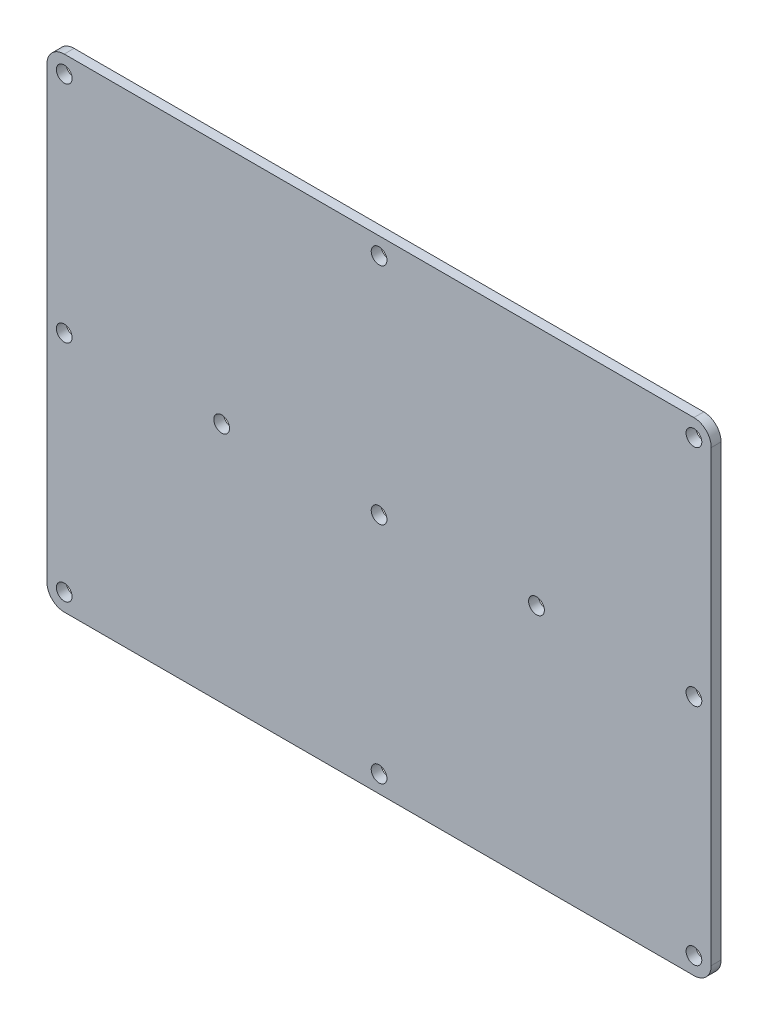
SolidWorks part; units mm, degrees
ref_plane "Front Plane" through (0, 0, 0) normal (0, 0, 1) x (1, 0, 0)
ref_plane "Top Plane" through (0, 0, 0) normal (0, 1, 0) x (1, 0, 0)
ref_plane "Right Plane" through (0, 0, 0) normal (1, 0, 0) x (0, 0, -1)
sketch "Sketch1" plane through (0, 0, 0) normal (0, 0, 1) x (1, 0, 0)
  line L0 (-152.4, 127) -> (-76.2, 127) construction
  line L1 (-152.4, 152.4) -> (152.4, 152.4)
  line L2 (-152.4, 152.4) -> (-152.4, -152.4)
  line L3 (-152.4, -152.4) -> (152.4, -152.4)
  line L4 (152.4, 152.4) -> (152.4, -152.4)
  line L5 (-76.2, 127) -> (-25.4, 127) construction
  line L6 (-25.4, 127) -> (25.4, 127) construction
  line L7 (25.4, 127) -> (76.2, 127) construction
  line L8 (76.2, 127) -> (152.4, 127) construction
  line L9 (-152.4, 0) -> (152.4, 0) construction
  line L10 (0, 152.4) -> (0, -152.4) construction
  line L11 (-118.11, 152.4) -> (-118.11, -152.4) construction
  line L12 (-152.4, -127) -> (152.4, -127) construction
  line L13 (127, 152.4) -> (127, -152.4) construction
  line L14 (-50.8, 152.4) -> (-50.8, -152.4) construction
  line L15 (50.8, 152.4) -> (50.8, -152.4) construction
  line L16 (-101.6, 152.4) -> (-101.6, -152.4) construction
  line L17 (-95.25, 66.04) -> (-57.15, 66.04) construction
  line L18 (-95.25, 66.04) -> (-95.25, -66.04) construction
  line L19 (-95.25, -66.04) -> (-57.15, -66.04) construction
  line L20 (-57.15, 66.04) -> (-57.15, -66.04) construction
  line L21 (-44.45, 66.04) -> (-6.35, 66.04) construction
  line L22 (-44.45, 66.04) -> (-44.45, -66.04) construction
  line L23 (-44.45, -66.04) -> (-6.35, -66.04) construction
  line L24 (-6.35, 66.04) -> (-6.35, -66.04) construction
  line L25 (6.35, 66.04) -> (44.45, 66.04) construction
  line L26 (6.35, 66.04) -> (6.35, -66.04) construction
  line L27 (6.35, -66.04) -> (44.45, -66.04) construction
  line L28 (44.45, 66.04) -> (44.45, -66.04) construction
  line L29 (57.15, 66.04) -> (95.25, 66.04) construction
  line L30 (57.15, 66.04) -> (57.15, -66.04) construction
  line L31 (57.15, -66.04) -> (95.25, -66.04) construction
  line L32 (95.25, 66.04) -> (95.25, -66.04) construction
  line L33 (101.6, 152.4) -> (101.6, -152.4) construction
  line L34 (-152.4, 120.65) -> (152.4, 120.65) construction
  line L35 (-101.6, 39.7057) -> (-95.25, 39.7057) construction
  line L36 (-57.15, 39.7057) -> (-50.8, 39.7057) construction
  line L37 (-76.2, 66.04) -> (-76.2, 0) construction
  line L38 (-76.2, 0) -> (-76.2, -66.04) construction
  line L39 (-152.4, 72.39) -> (152.4, 72.39) construction
  line L40 (-152.4, -72.39) -> (152.4, -72.39) construction
  line L41 (-76.2, 66.04) -> (-76.2, 72.39) construction
  line L42 (-95.25, -66.04) -> (-95.25, -72.39) construction
  line L43 (95.25, 39.7057) -> (101.6, 39.7057) construction
  line L44 (-95.25, 111.76) -> (-57.15, 111.76) construction
  line L45 (-57.15, 111.76) -> (-57.15, 118.4779) construction
  line L46 (-94.0266, 120.65) -> (-78.1749, 130.2582) construction
  line L47 (-95.25, 111.76) -> (-95.25, 118.4779) construction
  line L48 (-58.3734, 120.65) -> (-74.2251, 130.2582) construction
  line L49 (-107.3169, 130.81) -> (-83.1894, 130.81) construction
  line L50 (-6.35, 111.76) -> (-6.35, 118.4779) construction
  line L51 (-7.5734, 120.65) -> (-23.4251, 130.2582) construction
  line L52 (-43.2266, 120.65) -> (-27.3749, 130.2582) construction
  line L53 (-44.45, 111.76) -> (-44.45, 118.4779) construction
  line L54 (-6.35, 111.76) -> (-44.45, 111.76) construction
  line L55 (44.45, 111.76) -> (44.45, 118.4779) construction
  line L56 (43.2266, 120.65) -> (27.3749, 130.2582) construction
  line L57 (7.5734, 120.65) -> (23.4251, 130.2582) construction
  line L58 (6.35, 111.76) -> (6.35, 118.4779) construction
  line L59 (6.35, 111.76) -> (44.45, 111.76) construction
  line L60 (95.25, 111.76) -> (57.15, 111.76) construction
  line L61 (95.25, 111.76) -> (95.25, 118.4779) construction
  line L62 (94.0266, 120.65) -> (78.1749, 130.2582) construction
  line L63 (58.3734, 120.65) -> (74.2251, 130.2582) construction
  line L64 (57.15, 111.76) -> (57.15, 118.4779) construction
  line L65 (-95.25, -111.76) -> (-95.25, -118.4779) construction
  line L66 (-94.0266, -120.65) -> (-78.1749, -130.2582) construction
  line L67 (-58.3734, -120.65) -> (-74.2251, -130.2582) construction
  line L68 (-95.25, -111.76) -> (-57.15, -111.76) construction
  line L69 (-57.15, -111.76) -> (-57.15, -118.4779) construction
  line L70 (-44.45, -111.76) -> (-44.45, -118.4779) construction
  line L71 (-43.2266, -120.65) -> (-27.3749, -130.2582) construction
  line L72 (-6.35, -111.76) -> (-44.45, -111.76) construction
  line L73 (-7.5734, -120.65) -> (-23.4251, -130.2582) construction
  line L74 (-6.35, -111.76) -> (-6.35, -118.4779) construction
  line L75 (6.35, -111.76) -> (6.35, -118.4779) construction
  line L76 (7.5734, -120.65) -> (23.4251, -130.2582) construction
  line L77 (43.2266, -120.65) -> (27.3749, -130.2582) construction
  line L78 (6.35, -111.76) -> (44.45, -111.76) construction
  line L79 (44.45, -111.76) -> (44.45, -118.4779) construction
  line L80 (57.15, -111.76) -> (57.15, -118.4779) construction
  line L81 (58.3734, -120.65) -> (74.2251, -130.2582) construction
  line L82 (94.0266, -120.65) -> (78.1749, -130.2582) construction
  line L83 (95.25, -111.76) -> (57.15, -111.76) construction
  line L84 (95.25, -111.76) -> (95.25, -118.4779) construction
  line L85 (-152.4, 97.79) -> (152.4, 97.79) construction
  line L86 (-50.8, 39.7057) -> (-44.45, 39.7057) construction
  line L87 (-127, 152.4) -> (-127, -152.4) construction
  line L89 (-95.25, 101.6) -> (-92.3192, 101.6) construction
  line L90 (-95.25, 101.6) -> (-95.25, -101.6) construction
  line L96 (-90.8538, 101.6) -> (-90.8538, 68.58) construction
  line L97 (-89.3885, 101.6) -> (-89.3885, 68.58) construction
  line L98 (-92.3192, 101.6) -> (-92.3192, 68.58) construction
  line L99 (-83.5269, 101.6) -> (-83.5269, 68.58) construction
  line L100 (-86.4577, 101.6) -> (-86.4577, 68.58) construction
  line L101 (-89.3885, 101.6) -> (-86.4577, 101.6) construction
  line L102 (-77.6654, 101.6) -> (-77.6654, 68.58) construction
  line L103 (-80.5962, 101.6) -> (-80.5962, 68.58) construction
  line L104 (-83.5269, 101.6) -> (-80.5962, 101.6) construction
  line L105 (-71.8038, 101.6) -> (-71.8038, 68.58) construction
  line L106 (-74.7346, 101.6) -> (-74.7346, 68.58) construction
  line L107 (-77.6654, 101.6) -> (-74.7346, 101.6) construction
  line L108 (-65.9423, 101.6) -> (-65.9423, 68.58) construction
  line L109 (-68.8731, 101.6) -> (-68.8731, 68.58) construction
  line L110 (-71.8038, 101.6) -> (-68.8731, 101.6) construction
  line L111 (-60.0808, 101.6) -> (-60.0808, 68.58) construction
  line L112 (-63.0115, 101.6) -> (-63.0115, 68.58) construction
  line L113 (-65.9423, 101.6) -> (-63.0115, 101.6) construction
  line L114 (-57.15, -101.6) -> (-57.15, 101.6) construction
  line L115 (-60.0808, 101.6) -> (-57.15, 101.6) construction
  line L116 (-92.3192, 68.58) -> (-89.3885, 68.58) construction
  line L117 (-60.0808, -101.6) -> (-57.15, -101.6) construction
  line L118 (-60.0808, -101.6) -> (-60.0808, -68.58) construction
  line L119 (-63.0115, -101.6) -> (-63.0115, -68.58) construction
  line L120 (-65.9423, -101.6) -> (-65.9423, -68.58) construction
  line L121 (-65.9423, -101.6) -> (-63.0115, -101.6) construction
  line L122 (-68.8731, -101.6) -> (-68.8731, -68.58) construction
  line L123 (-71.8038, -101.6) -> (-68.8731, -101.6) construction
  line L124 (-71.8038, -101.6) -> (-71.8038, -68.58) construction
  line L125 (-74.7346, -101.6) -> (-74.7346, -68.58) construction
  line L126 (-77.6654, -101.6) -> (-74.7346, -101.6) construction
  line L127 (-77.6654, -101.6) -> (-77.6654, -68.58) construction
  line L128 (-80.5962, -101.6) -> (-80.5962, -68.58) construction
  line L129 (-83.5269, -101.6) -> (-80.5962, -101.6) construction
  line L130 (-83.5269, -101.6) -> (-83.5269, -68.58) construction
  line L131 (-86.4577, -101.6) -> (-86.4577, -68.58) construction
  line L132 (-89.3885, -101.6) -> (-86.4577, -101.6) construction
  line L133 (-89.3885, -101.6) -> (-89.3885, -68.58) construction
  line L134 (-92.3192, -101.6) -> (-92.3192, -68.58) construction
  line L135 (-95.25, -101.6) -> (-92.3192, -101.6) construction
  line L136 (-9.2808, 68.58) -> (-12.2115, 68.58) construction
  line L137 (6.35, 66.04) -> (44.45, 66.04) construction
  line L138 (-6.35, -66.04) -> (-6.35, -72.39) construction
  line L139 (-25.4, 66.04) -> (-25.4, 72.39) construction
  line L140 (-25.4, 0) -> (-25.4, -66.04) construction
  line L141 (-25.4, 66.04) -> (-25.4, 0) construction
  line L142 (-44.45, 66.04) -> (-44.45, -66.04) construction
  line L143 (-6.35, -66.04) -> (-44.45, -66.04) construction
  line L144 (-6.35, 66.04) -> (-6.35, -66.04) construction
  line L145 (-6.35, 66.04) -> (-44.45, 66.04) construction
  line L146 (-6.35, -101.6) -> (-9.2808, -101.6) construction
  line L147 (-9.2808, -101.6) -> (-9.2808, -68.58) construction
  line L148 (-12.2115, -101.6) -> (-12.2115, -68.58) construction
  line L149 (-12.2115, -101.6) -> (-15.1423, -101.6) construction
  line L150 (-15.1423, -101.6) -> (-15.1423, -68.58) construction
  line L151 (-18.0731, -101.6) -> (-18.0731, -68.58) construction
  line L152 (-18.0731, -101.6) -> (-21.0038, -101.6) construction
  line L153 (-21.0038, -101.6) -> (-21.0038, -68.58) construction
  line L154 (-23.9346, -101.6) -> (-23.9346, -68.58) construction
  line L155 (-23.9346, -101.6) -> (-26.8654, -101.6) construction
  line L156 (-26.8654, -101.6) -> (-26.8654, -68.58) construction
  line L157 (-29.7962, -101.6) -> (-29.7962, -68.58) construction
  line L158 (-29.7962, -101.6) -> (-32.7269, -101.6) construction
  line L159 (-32.7269, -101.6) -> (-32.7269, -68.58) construction
  line L160 (-35.6577, -101.6) -> (-38.5885, -101.6) construction
  line L161 (-35.6577, -101.6) -> (-35.6577, -68.58) construction
  line L162 (-38.5885, -101.6) -> (-38.5885, -68.58) construction
  line L163 (-41.5192, -101.6) -> (-41.5192, -68.58) construction
  line L164 (-41.5192, -101.6) -> (-44.45, -101.6) construction
  line L165 (-41.5192, 101.6) -> (-44.45, 101.6) construction
  line L166 (-44.45, -101.6) -> (-44.45, 101.6) construction
  line L167 (-35.6577, 101.6) -> (-38.5885, 101.6) construction
  line L168 (-38.5885, 101.6) -> (-38.5885, 68.58) construction
  line L169 (-41.5192, 101.6) -> (-41.5192, 68.58) construction
  line L170 (-29.7962, 101.6) -> (-32.7269, 101.6) construction
  line L171 (-32.7269, 101.6) -> (-32.7269, 68.58) construction
  line L172 (-35.6577, 101.6) -> (-35.6577, 68.58) construction
  line L173 (-23.9346, 101.6) -> (-26.8654, 101.6) construction
  line L174 (-26.8654, 101.6) -> (-26.8654, 68.58) construction
  line L175 (-29.7962, 101.6) -> (-29.7962, 68.58) construction
  line L176 (-18.0731, 101.6) -> (-21.0038, 101.6) construction
  line L177 (-21.0038, 101.6) -> (-21.0038, 68.58) construction
  line L178 (-23.9346, 101.6) -> (-23.9346, 68.58) construction
  line L179 (-12.2115, 101.6) -> (-15.1423, 101.6) construction
  line L180 (-15.1423, 101.6) -> (-15.1423, 68.58) construction
  line L181 (-18.0731, 101.6) -> (-18.0731, 68.58) construction
  line L182 (-9.2808, 101.6) -> (-9.2808, 68.58) construction
  line L183 (-12.2115, 101.6) -> (-12.2115, 68.58) construction
  line L184 (-6.35, 101.6) -> (-6.35, -101.6) construction
  line L185 (-6.35, 101.6) -> (-9.2808, 101.6) construction
  line L186 (6.35, 66.04) -> (6.35, -66.04) construction
  line L187 (6.35, -66.04) -> (44.45, -66.04) construction
  line L188 (44.45, 66.04) -> (44.45, -66.04) construction
  line L189 (25.4, 66.04) -> (25.4, 0) construction
  line L190 (25.4, 0) -> (25.4, -66.04) construction
  line L191 (25.4, 66.04) -> (25.4, 72.39) construction
  line L192 (6.35, -66.04) -> (6.35, -72.39) construction
  line L193 (9.2808, 68.58) -> (12.2115, 68.58) construction
  line L194 (6.35, 66.04) -> (6.35, -66.04) construction
  line L195 (44.45, -66.04) -> (6.35, -66.04) construction
  line L196 (44.45, 66.04) -> (44.45, -66.04) construction
  line L197 (44.45, 66.04) -> (6.35, 66.04) construction
  line L198 (6.35, 101.6) -> (9.2808, 101.6) construction
  line L199 (6.35, 101.6) -> (6.35, -101.6) construction
  line L200 (12.2115, 101.6) -> (12.2115, 68.58) construction
  line L201 (9.2808, 101.6) -> (9.2808, 68.58) construction
  line L202 (18.0731, 101.6) -> (18.0731, 68.58) construction
  line L203 (15.1423, 101.6) -> (15.1423, 68.58) construction
  line L204 (12.2115, 101.6) -> (15.1423, 101.6) construction
  line L205 (23.9346, 101.6) -> (23.9346, 68.58) construction
  line L206 (21.0038, 101.6) -> (21.0038, 68.58) construction
  line L207 (18.0731, 101.6) -> (21.0038, 101.6) construction
  line L208 (29.7962, 101.6) -> (29.7962, 68.58) construction
  line L209 (26.8654, 101.6) -> (26.8654, 68.58) construction
  line L210 (23.9346, 101.6) -> (26.8654, 101.6) construction
  line L211 (35.6577, 101.6) -> (35.6577, 68.58) construction
  line L212 (32.7269, 101.6) -> (32.7269, 68.58) construction
  line L213 (29.7962, 101.6) -> (32.7269, 101.6) construction
  line L214 (41.5192, 101.6) -> (41.5192, 68.58) construction
  line L215 (38.5885, 101.6) -> (38.5885, 68.58) construction
  line L216 (35.6577, 101.6) -> (38.5885, 101.6) construction
  line L217 (44.45, -101.6) -> (44.45, 101.6) construction
  line L218 (41.5192, 101.6) -> (44.45, 101.6) construction
  line L219 (41.5192, -101.6) -> (44.45, -101.6) construction
  line L220 (41.5192, -101.6) -> (41.5192, -68.58) construction
  line L221 (38.5885, -101.6) -> (38.5885, -68.58) construction
  line L222 (35.6577, -101.6) -> (35.6577, -68.58) construction
  line L223 (35.6577, -101.6) -> (38.5885, -101.6) construction
  line L224 (32.7269, -101.6) -> (32.7269, -68.58) construction
  line L225 (29.7962, -101.6) -> (32.7269, -101.6) construction
  line L226 (29.7962, -101.6) -> (29.7962, -68.58) construction
  line L227 (26.8654, -101.6) -> (26.8654, -68.58) construction
  line L228 (23.9346, -101.6) -> (26.8654, -101.6) construction
  line L229 (23.9346, -101.6) -> (23.9346, -68.58) construction
  line L230 (21.0038, -101.6) -> (21.0038, -68.58) construction
  line L231 (18.0731, -101.6) -> (21.0038, -101.6) construction
  line L232 (18.0731, -101.6) -> (18.0731, -68.58) construction
  line L233 (15.1423, -101.6) -> (15.1423, -68.58) construction
  line L234 (12.2115, -101.6) -> (15.1423, -101.6) construction
  line L235 (12.2115, -101.6) -> (12.2115, -68.58) construction
  line L236 (9.2808, -101.6) -> (9.2808, -68.58) construction
  line L237 (6.35, -101.6) -> (9.2808, -101.6) construction
  line L238 (57.15, 66.04) -> (95.25, 66.04) construction
  line L239 (57.15, 66.04) -> (57.15, -66.04) construction
  line L240 (57.15, -66.04) -> (95.25, -66.04) construction
  line L241 (95.25, 66.04) -> (95.25, -66.04) construction
  line L242 (92.3192, 68.58) -> (89.3885, 68.58) construction
  line L243 (95.25, -66.04) -> (95.25, -72.39) construction
  line L244 (76.2, 66.04) -> (76.2, 72.39) construction
  line L245 (76.2, 0) -> (76.2, -66.04) construction
  line L246 (76.2, 66.04) -> (76.2, 0) construction
  line L247 (57.15, 66.04) -> (57.15, -66.04) construction
  line L248 (95.25, -66.04) -> (57.15, -66.04) construction
  line L249 (95.25, 66.04) -> (95.25, -66.04) construction
  line L250 (95.25, 66.04) -> (57.15, 66.04) construction
  line L251 (57.15, 66.04) -> (57.15, -66.04) construction
  line L252 (95.25, -66.04) -> (57.15, -66.04) construction
  line L253 (95.25, 66.04) -> (95.25, -66.04) construction
  line L254 (95.25, 66.04) -> (57.15, 66.04) construction
  line L255 (95.25, -101.6) -> (92.3192, -101.6) construction
  line L256 (92.3192, -101.6) -> (92.3192, -68.58) construction
  line L257 (89.3885, -101.6) -> (89.3885, -68.58) construction
  line L258 (89.3885, -101.6) -> (86.4577, -101.6) construction
  line L259 (86.4577, -101.6) -> (86.4577, -68.58) construction
  line L260 (83.5269, -101.6) -> (83.5269, -68.58) construction
  line L261 (83.5269, -101.6) -> (80.5962, -101.6) construction
  line L262 (80.5962, -101.6) -> (80.5962, -68.58) construction
  line L263 (77.6654, -101.6) -> (77.6654, -68.58) construction
  line L264 (77.6654, -101.6) -> (74.7346, -101.6) construction
  line L265 (74.7346, -101.6) -> (74.7346, -68.58) construction
  line L266 (71.8038, -101.6) -> (71.8038, -68.58) construction
  line L267 (71.8038, -101.6) -> (68.8731, -101.6) construction
  line L268 (68.8731, -101.6) -> (68.8731, -68.58) construction
  line L269 (65.9423, -101.6) -> (63.0115, -101.6) construction
  line L270 (65.9423, -101.6) -> (65.9423, -68.58) construction
  line L271 (63.0115, -101.6) -> (63.0115, -68.58) construction
  line L272 (60.0808, -101.6) -> (60.0808, -68.58) construction
  line L273 (60.0808, -101.6) -> (57.15, -101.6) construction
  line L274 (60.0808, 101.6) -> (57.15, 101.6) construction
  line L275 (57.15, -101.6) -> (57.15, 101.6) construction
  line L276 (65.9423, 101.6) -> (63.0115, 101.6) construction
  line L277 (63.0115, 101.6) -> (63.0115, 68.58) construction
  line L278 (60.0808, 101.6) -> (60.0808, 68.58) construction
  line L279 (71.8038, 101.6) -> (68.8731, 101.6) construction
  line L280 (68.8731, 101.6) -> (68.8731, 68.58) construction
  line L281 (65.9423, 101.6) -> (65.9423, 68.58) construction
  line L282 (77.6654, 101.6) -> (74.7346, 101.6) construction
  line L283 (74.7346, 101.6) -> (74.7346, 68.58) construction
  line L284 (71.8038, 101.6) -> (71.8038, 68.58) construction
  line L285 (83.5269, 101.6) -> (80.5962, 101.6) construction
  line L286 (80.5962, 101.6) -> (80.5962, 68.58) construction
  line L287 (77.6654, 101.6) -> (77.6654, 68.58) construction
  line L288 (89.3885, 101.6) -> (86.4577, 101.6) construction
  line L289 (86.4577, 101.6) -> (86.4577, 68.58) construction
  line L290 (83.5269, 101.6) -> (83.5269, 68.58) construction
  line L291 (92.3192, 101.6) -> (92.3192, 68.58) construction
  line L292 (89.3885, 101.6) -> (89.3885, 68.58) construction
  line L293 (95.25, 101.6) -> (95.25, -101.6) construction
  line L294 (95.25, 101.6) -> (92.3192, 101.6) construction
  line L295 (-101.6, 39.7057) -> (-107.95, 39.7057) construction
  line L296 (-101.6, 78.74) -> (101.6, 78.74)
  line L298 (-101.6, -78.74) -> (101.6, -78.74)
  line L300 (-97.0611, 78.74) -> (-97.0611, 72.39) construction
  line L301 (-110.49, 22.225) -> (-120.65, 22.225) construction
  line L302 (-127, 15.875) -> (-127, -15.875) construction
  line L303 (-120.65, -22.225) -> (-110.49, -22.225) construction
  line L304 (-90.964, 120.65) -> (-61.436, 120.65) construction
  line L305 (-90.964, 122.2375) -> (-61.436, 122.2375) construction
  line L306 (-90.964, 119.0625) -> (-61.436, 119.0625) construction
  line L307 (-10.636, 120.65) -> (-40.164, 120.65) construction
  line L308 (-10.636, 122.2375) -> (-40.164, 122.2375) construction
  line L309 (-10.636, 119.0625) -> (-40.164, 119.0625) construction
  line L310 (10.636, 120.65) -> (40.164, 120.65) construction
  line L311 (10.636, 122.2375) -> (40.164, 122.2375) construction
  line L312 (10.636, 119.0625) -> (40.164, 119.0625) construction
  line L313 (90.964, 120.65) -> (61.436, 120.65) construction
  line L314 (90.964, 122.2375) -> (61.436, 122.2375) construction
  line L315 (90.964, 119.0625) -> (61.436, 119.0625) construction
  line L316 (90.964, -120.65) -> (61.436, -120.65) construction
  line L317 (90.964, -122.2375) -> (61.436, -122.2375) construction
  line L318 (90.964, -119.0625) -> (61.436, -119.0625) construction
  line L319 (10.636, -120.65) -> (40.164, -120.65) construction
  line L320 (10.636, -122.2375) -> (40.164, -122.2375) construction
  line L321 (10.636, -119.0625) -> (40.164, -119.0625) construction
  line L322 (-10.636, -120.65) -> (-40.164, -120.65) construction
  line L323 (-10.636, -122.2375) -> (-40.164, -122.2375) construction
  line L324 (-10.636, -119.0625) -> (-40.164, -119.0625) construction
  line L325 (-90.964, -120.65) -> (-61.436, -120.65) construction
  line L326 (-90.964, -122.2375) -> (-61.436, -122.2375) construction
  line L327 (-90.964, -119.0625) -> (-61.436, -119.0625) construction
  line L328 (-6.35, 111.125) -> (-6.35, 92.075) construction
  line L329 (-95.25, 111.125) -> (-57.15, 111.125) construction
  line L330 (-95.25, 111.125) -> (-95.25, 92.075) construction
  line L331 (-95.25, 92.075) -> (-57.15, 92.075) construction
  line L332 (-57.15, 111.125) -> (-57.15, 92.075) construction
  line L333 (-6.35, 111.125) -> (-44.45, 111.125) construction
  line L334 (-44.45, 111.125) -> (-44.45, 92.075) construction
  line L335 (-6.35, 92.075) -> (-44.45, 92.075) construction
  line L336 (95.25, 92.075) -> (57.15, 92.075) construction
  line L337 (95.25, 111.125) -> (95.25, 92.075)
  line L338 (95.25, 111.125) -> (57.15, 111.125) construction
  line L339 (57.15, 111.125) -> (57.15, 92.075) construction
  line L340 (44.45, 111.125) -> (44.45, 92.075) construction
  line L341 (6.35, 92.075) -> (44.45, 92.075) construction
  line L342 (6.35, 111.125) -> (44.45, 111.125) construction
  line L343 (6.35, 111.125) -> (6.35, 92.075) construction
  line L344 (-95.25, -92.075) -> (-57.15, -92.075) construction
  line L345 (-95.25, -111.125) -> (-95.25, -92.075) construction
  line L346 (-95.25, -111.125) -> (-57.15, -111.125) construction
  line L347 (-57.15, -111.125) -> (-57.15, -92.075) construction
  line L348 (-44.45, -111.125) -> (-44.45, -92.075) construction
  line L349 (-6.35, -92.075) -> (-44.45, -92.075) construction
  line L350 (-6.35, -111.125) -> (-44.45, -111.125) construction
  line L351 (-6.35, -111.125) -> (-6.35, -92.075) construction
  line L352 (6.35, -111.125) -> (6.35, -92.075) construction
  line L353 (6.35, -92.075) -> (44.45, -92.075) construction
  line L354 (6.35, -111.125) -> (44.45, -111.125) construction
  line L355 (44.45, -111.125) -> (44.45, -92.075) construction
  line L356 (57.15, -111.125) -> (57.15, -92.075) construction
  line L357 (95.25, -111.125) -> (57.15, -111.125) construction
  line L358 (95.25, -111.125) -> (95.25, -92.075) construction
  line L359 (95.25, -92.075) -> (57.15, -92.075) construction
  line L360 (-107.95, 72.39) -> (-107.95, 24.765)
  line L361 (-107.95, 22.225) -> (-107.95, -22.225) construction
  line L362 (-107.95, -24.765) -> (-107.95, -72.39)
  line L363 (3.659, 78.74) -> (3.659, -78.74) construction
  line L364 (120.65, -22.225) -> (110.49, -22.225) construction
  line L365 (127, 15.875) -> (127, -15.875) construction
  line L366 (110.49, 22.225) -> (120.65, 22.225) construction
  line L367 (107.95, 72.39) -> (107.95, 24.765)
  line L368 (107.95, -24.765) -> (107.95, -72.39)
  line L369 (-107.95, 24.765) -> (-107.95, -24.765)
  line L370 (107.95, 24.765) -> (107.95, -24.765)
  line L371 (-101.6, 77.978) -> (101.6, 77.978)
  line L372 (107.188, 72.39) -> (107.188, 24.765)
  line L373 (107.188, 24.765) -> (107.188, -24.765)
  line L374 (107.188, -24.765) -> (107.188, -72.39)
  line L375 (-101.6, -77.978) -> (101.6, -77.978)
  line L376 (-107.188, -24.765) -> (-107.188, -72.39)
  line L377 (-107.188, 24.765) -> (-107.188, -24.765)
  line L378 (-107.188, 72.39) -> (-107.188, 24.765)
  circle A0 centre (-76.2, 127) radius 2.5527 construction
  circle A1 centre (-25.4, 127) radius 2.5527 construction
  circle A2 centre (25.4, 127) radius 2.5527 construction
  circle A3 centre (76.2, 127) radius 2.5527 construction
  circle A4 centre (-101.6, 0) radius 2.54
  circle A5 centre (-50.8, 0) radius 2.54
  circle A6 centre (0, 0) radius 2.54
  circle A7 centre (101.6, 0) radius 2.54
  circle A8 centre (50.8, 0) radius 2.54
  circle A9 centre (-50.8, 127) radius 2.54
  circle A10 centre (0, 127) radius 2.54
  circle A11 centre (50.8, 127) radius 2.54
  circle A12 centre (-101.6, 72.39) radius 2.54
  circle A13 centre (0, 72.39) radius 2.54
  circle A14 centre (101.6, 72.39) radius 2.54
  circle A15 centre (-101.6, -72.39) radius 2.54
  circle A16 centre (0, -72.39) radius 2.54
  circle A17 centre (101.6, -72.39) radius 2.54
  arc A18 (-74.2251, 130.2582) -> (-78.1749, 130.2582) centre (-76.2, 127) ccw construction
  arc A19 (-57.15, 118.4779) -> (-58.3734, 120.65) centre (-59.69, 118.4779) ccw construction
  arc A20 (-95.25, 118.4779) -> (-94.0266, 120.65) centre (-92.71, 118.4779) cw construction
  arc A21 (-6.35, 118.4779) -> (-7.5734, 120.65) centre (-8.89, 118.4779) ccw construction
  arc A22 (-27.3749, 130.2582) -> (-23.4251, 130.2582) centre (-25.4, 127) cw construction
  arc A23 (-44.45, 118.4779) -> (-43.2266, 120.65) centre (-41.91, 118.4779) cw construction
  arc A24 (44.45, 118.4779) -> (43.2266, 120.65) centre (41.91, 118.4779) ccw construction
  arc A25 (27.3749, 130.2582) -> (23.4251, 130.2582) centre (25.4, 127) ccw construction
  arc A26 (6.35, 118.4779) -> (7.5734, 120.65) centre (8.89, 118.4779) cw construction
  arc A27 (95.25, 118.4779) -> (94.0266, 120.65) centre (92.71, 118.4779) ccw construction
  arc A28 (74.2251, 130.2582) -> (78.1749, 130.2582) centre (76.2, 127) cw construction
  arc A29 (57.15, 118.4779) -> (58.3734, 120.65) centre (59.69, 118.4779) cw construction
  circle A30 centre (-76.2, -127) radius 2.5527 construction
  circle A31 centre (-25.4, -127) radius 2.5527 construction
  circle A32 centre (25.4, -127) radius 2.5527 construction
  circle A33 centre (76.2, -127) radius 2.5527 construction
  arc A34 (-95.25, -118.4779) -> (-94.0266, -120.65) centre (-92.71, -118.4779) ccw construction
  arc A35 (-74.2251, -130.2582) -> (-78.1749, -130.2582) centre (-76.2, -127) cw construction
  arc A36 (-57.15, -118.4779) -> (-58.3734, -120.65) centre (-59.69, -118.4779) cw construction
  arc A37 (-44.45, -118.4779) -> (-43.2266, -120.65) centre (-41.91, -118.4779) ccw construction
  arc A38 (-27.3749, -130.2582) -> (-23.4251, -130.2582) centre (-25.4, -127) ccw construction
  arc A39 (-6.35, -118.4779) -> (-7.5734, -120.65) centre (-8.89, -118.4779) cw construction
  arc A40 (6.35, -118.4779) -> (7.5734, -120.65) centre (8.89, -118.4779) ccw construction
  arc A41 (27.3749, -130.2582) -> (23.4251, -130.2582) centre (25.4, -127) cw construction
  arc A42 (44.45, -118.4779) -> (43.2266, -120.65) centre (41.91, -118.4779) cw construction
  arc A43 (57.15, -118.4779) -> (58.3734, -120.65) centre (59.69, -118.4779) ccw construction
  arc A44 (74.2251, -130.2582) -> (78.1749, -130.2582) centre (76.2, -127) ccw construction
  arc A45 (95.25, -118.4779) -> (94.0266, -120.65) centre (92.71, -118.4779) cw construction
  circle A46 centre (50.8, -127) radius 2.54
  circle A47 centre (0, -127) radius 2.54
  circle A48 centre (-50.8, -127) radius 2.54
  circle A49 centre (-101.6, 97.79) radius 2.54
  circle A50 centre (0, 97.79) radius 2.54
  circle A51 centre (101.6, 97.79) radius 2.54
  circle A52 centre (101.6, 127) radius 2.54
  circle A53 centre (-101.6, 127) radius 2.54
  circle A54 centre (-118.11, 33.02) radius 2.54
  circle A55 centre (127, 33.02) radius 2.54
  circle A56 centre (-101.6, -127) radius 2.54
  circle A57 centre (101.6, -127) radius 2.54
  circle A58 centre (101.6, -97.79) radius 2.54
  circle A59 centre (0, -97.79) radius 2.54
  circle A60 centre (-101.6, -97.79) radius 2.54
  circle A61 centre (-118.11, -33.02) radius 2.54
  circle A62 centre (127, -33.02) radius 2.54
  circle A63 centre (-139.7, 139.7) radius 3.2639
  circle A64 centre (-139.7, 0) radius 3.2639
  circle A65 centre (-139.7, -139.7) radius 3.2639
  circle A66 centre (139.7, -139.7) radius 3.2639
  circle A67 centre (139.7, 0) radius 3.2639
  circle A68 centre (139.7, 139.7) radius 3.2639
  arc A70 (-92.3192, 68.58) -> (-89.3885, 68.58) centre (-90.8538, 68.58) ccw construction
  arc A71 (-86.4577, 68.58) -> (-83.5269, 68.58) centre (-84.9923, 68.58) ccw construction
  arc A72 (-80.5962, 68.58) -> (-77.6654, 68.58) centre (-79.1308, 68.58) ccw construction
  arc A73 (-74.7346, 68.58) -> (-71.8038, 68.58) centre (-73.2692, 68.58) ccw construction
  arc A74 (-68.8731, 68.58) -> (-65.9423, 68.58) centre (-67.4077, 68.58) ccw construction
  arc A75 (-63.0115, 68.58) -> (-60.0808, 68.58) centre (-61.5462, 68.58) ccw construction
  arc A76 (-63.0115, -68.58) -> (-60.0808, -68.58) centre (-61.5462, -68.58) cw construction
  arc A77 (-68.8731, -68.58) -> (-65.9423, -68.58) centre (-67.4077, -68.58) cw construction
  arc A78 (-74.7346, -68.58) -> (-71.8038, -68.58) centre (-73.2692, -68.58) cw construction
  arc A79 (-80.5962, -68.58) -> (-77.6654, -68.58) centre (-79.1308, -68.58) cw construction
  arc A80 (-86.4577, -68.58) -> (-83.5269, -68.58) centre (-84.9923, -68.58) cw construction
  arc A81 (-92.3192, -68.58) -> (-89.3885, -68.58) centre (-90.8538, -68.58) cw construction
  arc A82 (-9.2808, -68.58) -> (-12.2115, -68.58) centre (-10.7462, -68.58) ccw construction
  arc A83 (-15.1423, -68.58) -> (-18.0731, -68.58) centre (-16.6077, -68.58) ccw construction
  arc A84 (-21.0038, -68.58) -> (-23.9346, -68.58) centre (-22.4692, -68.58) ccw construction
  arc A85 (-26.8654, -68.58) -> (-29.7962, -68.58) centre (-28.3308, -68.58) ccw construction
  arc A86 (-32.7269, -68.58) -> (-35.6577, -68.58) centre (-34.1923, -68.58) ccw construction
  arc A87 (-38.5885, -68.58) -> (-41.5192, -68.58) centre (-40.0538, -68.58) ccw construction
  arc A88 (-38.5885, 68.58) -> (-41.5192, 68.58) centre (-40.0538, 68.58) cw construction
  arc A89 (-32.7269, 68.58) -> (-35.6577, 68.58) centre (-34.1923, 68.58) cw construction
  arc A90 (-26.8654, 68.58) -> (-29.7962, 68.58) centre (-28.3308, 68.58) cw construction
  arc A91 (-21.0038, 68.58) -> (-23.9346, 68.58) centre (-22.4692, 68.58) cw construction
  arc A92 (-15.1423, 68.58) -> (-18.0731, 68.58) centre (-16.6077, 68.58) cw construction
  arc A93 (-9.2808, 68.58) -> (-12.2115, 68.58) centre (-10.7462, 68.58) cw construction
  arc A94 (9.2808, 68.58) -> (12.2115, 68.58) centre (10.7462, 68.58) ccw construction
  arc A95 (15.1423, 68.58) -> (18.0731, 68.58) centre (16.6077, 68.58) ccw construction
  arc A96 (21.0038, 68.58) -> (23.9346, 68.58) centre (22.4692, 68.58) ccw construction
  arc A97 (26.8654, 68.58) -> (29.7962, 68.58) centre (28.3308, 68.58) ccw construction
  arc A98 (32.7269, 68.58) -> (35.6577, 68.58) centre (34.1923, 68.58) ccw construction
  arc A99 (38.5885, 68.58) -> (41.5192, 68.58) centre (40.0538, 68.58) ccw construction
  arc A100 (38.5885, -68.58) -> (41.5192, -68.58) centre (40.0538, -68.58) cw construction
  arc A101 (32.7269, -68.58) -> (35.6577, -68.58) centre (34.1923, -68.58) cw construction
  arc A102 (26.8654, -68.58) -> (29.7962, -68.58) centre (28.3308, -68.58) cw construction
  arc A103 (21.0038, -68.58) -> (23.9346, -68.58) centre (22.4692, -68.58) cw construction
  arc A104 (15.1423, -68.58) -> (18.0731, -68.58) centre (16.6077, -68.58) cw construction
  arc A105 (9.2808, -68.58) -> (12.2115, -68.58) centre (10.7462, -68.58) cw construction
  arc A106 (92.3192, -68.58) -> (89.3885, -68.58) centre (90.8538, -68.58) ccw construction
  arc A107 (86.4577, -68.58) -> (83.5269, -68.58) centre (84.9923, -68.58) ccw construction
  arc A108 (80.5962, -68.58) -> (77.6654, -68.58) centre (79.1308, -68.58) ccw construction
  arc A109 (74.7346, -68.58) -> (71.8038, -68.58) centre (73.2692, -68.58) ccw construction
  arc A110 (68.8731, -68.58) -> (65.9423, -68.58) centre (67.4077, -68.58) ccw construction
  arc A111 (63.0115, -68.58) -> (60.0808, -68.58) centre (61.5462, -68.58) ccw construction
  arc A112 (63.0115, 68.58) -> (60.0808, 68.58) centre (61.5462, 68.58) cw construction
  arc A113 (68.8731, 68.58) -> (65.9423, 68.58) centre (67.4077, 68.58) cw construction
  arc A114 (74.7346, 68.58) -> (71.8038, 68.58) centre (73.2692, 68.58) cw construction
  arc A115 (80.5962, 68.58) -> (77.6654, 68.58) centre (79.1308, 68.58) cw construction
  arc A116 (86.4577, 68.58) -> (83.5269, 68.58) centre (84.9923, 68.58) cw construction
  arc A117 (92.3192, 68.58) -> (89.3885, 68.58) centre (90.8538, 68.58) cw construction
  arc A118 (-101.6, 78.74) -> (-107.95, 72.39) centre (-101.6, 72.39) ccw
  arc A119 (-107.95, -72.39) -> (-101.6, -78.74) centre (-101.6, -72.39) ccw
  arc A120 (101.6, 78.74) -> (107.95, 72.39) centre (101.6, 72.39) cw
  arc A121 (101.6, -78.74) -> (107.95, -72.39) centre (101.6, -72.39) ccw
  arc A122 (-127, -15.875) -> (-120.65, -22.225) centre (-120.65, -15.875) ccw construction
  arc A123 (-120.65, 22.225) -> (-127, 15.875) centre (-120.65, 15.875) ccw construction
  arc A124 (-90.964, 122.2375) -> (-90.964, 119.0625) centre (-90.964, 120.65) ccw construction
  arc A125 (-61.436, 119.0625) -> (-61.436, 122.2375) centre (-61.436, 120.65) ccw construction
  arc A126 (-10.636, 122.2375) -> (-10.636, 119.0625) centre (-10.636, 120.65) cw construction
  arc A127 (-40.164, 119.0625) -> (-40.164, 122.2375) centre (-40.164, 120.65) cw construction
  arc A128 (10.636, 122.2375) -> (10.636, 119.0625) centre (10.636, 120.65) ccw construction
  arc A129 (40.164, 119.0625) -> (40.164, 122.2375) centre (40.164, 120.65) ccw construction
  arc A130 (90.964, 122.2375) -> (90.964, 119.0625) centre (90.964, 120.65) cw construction
  arc A131 (61.436, 119.0625) -> (61.436, 122.2375) centre (61.436, 120.65) cw construction
  arc A132 (90.964, -122.2375) -> (90.964, -119.0625) centre (90.964, -120.65) ccw construction
  arc A133 (61.436, -119.0625) -> (61.436, -122.2375) centre (61.436, -120.65) ccw construction
  arc A134 (10.636, -122.2375) -> (10.636, -119.0625) centre (10.636, -120.65) cw construction
  arc A135 (40.164, -119.0625) -> (40.164, -122.2375) centre (40.164, -120.65) cw construction
  arc A136 (-10.636, -122.2375) -> (-10.636, -119.0625) centre (-10.636, -120.65) ccw construction
  arc A137 (-40.164, -119.0625) -> (-40.164, -122.2375) centre (-40.164, -120.65) ccw construction
  arc A138 (-90.964, -122.2375) -> (-90.964, -119.0625) centre (-90.964, -120.65) cw construction
  arc A139 (-61.436, -119.0625) -> (-61.436, -122.2375) centre (-61.436, -120.65) cw construction
  arc A140 (-110.49, -22.225) -> (-107.95, -24.765) centre (-110.49, -24.765) cw construction
  arc A141 (-110.49, 22.225) -> (-107.95, 24.765) centre (-110.49, 24.765) ccw construction
  arc A142 (110.49, -22.225) -> (107.95, -24.765) centre (110.49, -24.765) ccw construction
  arc A143 (127, -15.875) -> (120.65, -22.225) centre (120.65, -15.875) cw construction
  arc A144 (120.65, 22.225) -> (127, 15.875) centre (120.65, 15.875) cw construction
  arc A145 (110.49, 22.225) -> (107.95, 24.765) centre (110.49, 24.765) cw construction
  arc A146 (101.6, 77.978) -> (107.188, 72.39) centre (101.6, 72.39) cw
  arc A147 (101.6, -77.978) -> (107.188, -72.39) centre (101.6, -72.39) ccw
  arc A148 (-107.188, -72.39) -> (-101.6, -77.978) centre (-101.6, -72.39) ccw
  arc A149 (-101.6, 77.978) -> (-107.188, 72.39) centre (-101.6, 72.39) ccw
  point P10 (-76.2, 111.76)
  point P63 (50.8, 127)
  point P95 (-76.2, 66.04)
  point P97 (-25.4, 66.04)
  point P99 (25.4, 66.04)
  point P101 (76.2, 66.04)
  point P116 (-95.25, 0)
  point P118 (-44.45, 0)
  point P119 (6.35, 0)
  point P120 (57.15, 0)
  point P219 (-76.2, 33.02)
  point P259 (0, 78.74)
  point P260 (3.659, 0)
  point P545 (-127, 0)
  point P548 (-127, -22.225)
  point P551 (-127, 22.225)
  point P554 (-76.2, 120.65)
  point P562 (-25.4, 120.65)
  point P569 (25.4, 120.65)
  point P576 (76.2, 120.65)
  point P583 (76.2, -120.65)
  point P590 (25.4, -120.65)
  point P597 (-25.4, -120.65)
  point P604 (-76.2, -120.65)
  point P612 (-57.15, 101.6)
  point P613 (-58.6154, 101.6)
  dimension "D1" = 5.1054
  dimension "D7" = 5.08
  dimension "D11" = 7.62
  dimension "D13" = 2.54
  dimension "D19" = 6.5278
  dimension "D25" = 6.35
  dimension "D26" = 6.35
  dimension "D27" = 6.35
  dimension "D29" = 6.35
  dimension "D32" = 2.54
  dimension "D2" = 25.4
  dimension "D3" = 50.8
  dimension "D4" = 25.4
  dimension "D5" = 25.4
  dimension "D6" = 25.4
  dimension "D8" = 38.1
  dimension "D9" = 31.75
  dimension "D10" = 132.08
  dimension "D12" = 19.05
  dimension "D14" = 25.4
  dimension "D15" = 304.8
  dimension "D16" = 304.8
  dimension "D17" = 8.89
  dimension "D18" = 12.7
  dimension "D20" = 12.7
  dimension "D21" = 12.7
  dimension "D23" = 33.02
  dimension "D24" = 10.16
  dimension "D28" = 44.45
  dimension "D30" = 3.175
  dimension "D31" = 19.05
  dimension "D33" = 0.762
  dimension "D22" = 6
extrude "Boss-Extrude1" add sketch "Sketch1" along normal blind 3.175 contours L371 A149 L378 L377 L376 A148 L375 A147 L374 L373 L372 A146 A4 A5 A6 A7 A8 A12 A13 A14 A15 A16 A17
